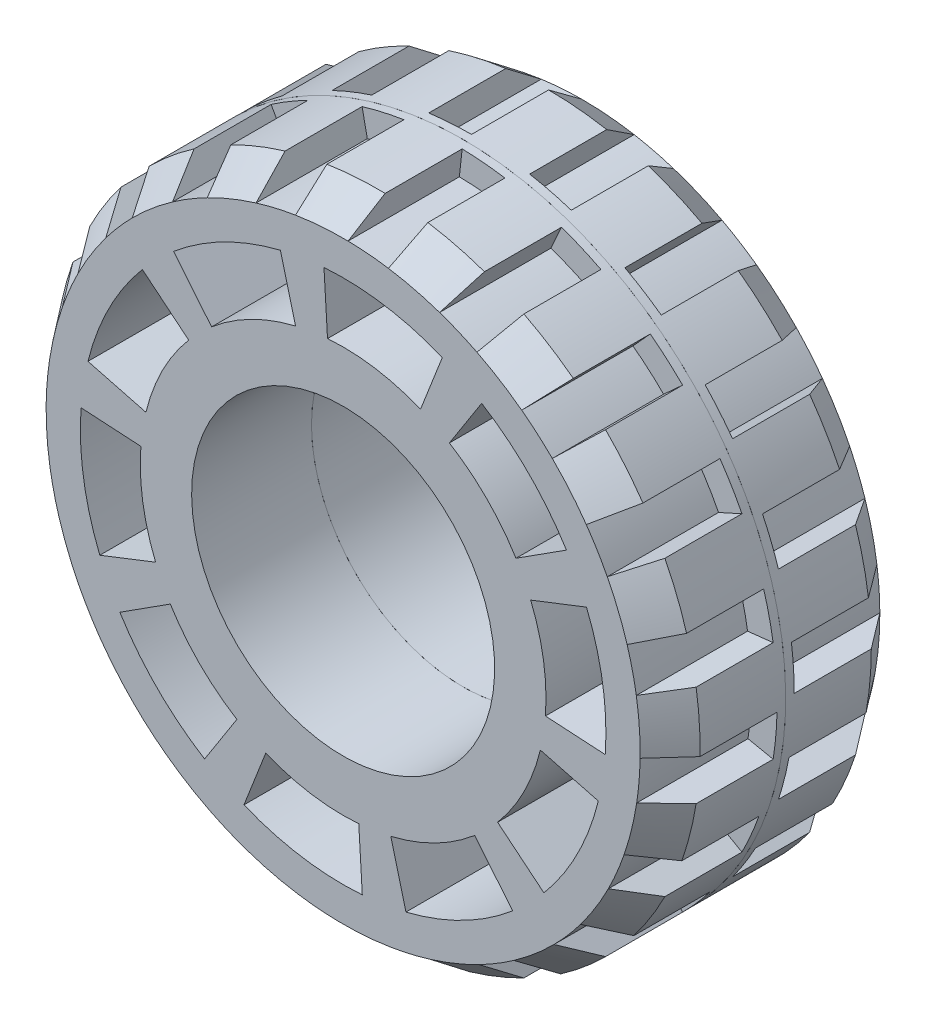
SolidWorks part; units mm, degrees
material "Rubber"
ref_plane "Front Plane" through (0, 0, 0) normal (0, 0, 1) x (1, 0, 0)
ref_plane "Top Plane" through (0, 0, 0) normal (0, 1, 0) x (1, 0, 0)
ref_plane "Right Plane" through (0, 0, 0) normal (1, 0, 0) x (0, 0, -1)
sketch "Sketch2" plane through (0, 0, 0) normal (1, 0, 0) x (0, 0, -1)
  line L0 (0, 8.85) -> (0, 18.85)
  line L1 (0, 18.85) -> (5, 18.85)
  line L2 (5, 18.85) -> (7, 17.35)
  line L3 (0, 8.85) -> (7, 8.85)
  line L4 (7, 17.35) -> (7, 8.85)
  line L5 (-10.899, 0) -> (29.6254, 0) construction
  dimension "D1" = 10
  dimension "D2" = 2.5
  dimension "D3" = 7
  dimension "D4" = 5
  dimension "D5" = 8.85
revolve "Revolve1" add sketch "Sketch2" angle 360 about L5
ref_plane "Plane2" through (0, 0, 0) normal (0, 0, 1) x (1, 0, 0)
sketch "Sketch4" plane through (0, 0, -7) normal (0, 0, -1) x (-1, 0, 0)
  line L0 (14.9457, 3.5) -> (11.5265, 2.75)
  line L1 (14.9457, -3.5) -> (11.5265, -2.75)
  arc A0 (14.9457, 3.5) -> (14.9457, -3.5) centre (0, 0) cw
  arc A1 (11.5265, 2.75) -> (11.5265, -2.75) centre (0, 0) cw
  circle A2 centre (0, 0) radius 18.85 construction
  point P6 (15.35, 0)
  point P7 (11.85, 0)
  dimension "D3" = 3.5
  dimension "D4" = 3.5
  dimension "D1" = 7
  dimension "D2" = 5.5
extrude "Cut-Extrude1" cut sketch "Sketch4" against normal offset from surface (5 mm away) 2 up to face at (8.85, 0, 0)
pattern_circular "CirPattern1" count 10 over 360 about axis through (0, 0, 0) along (0, 0, 1) of "Cut-Extrude1"
sketch "Sketch5" plane through (0, 0, -7) normal (0, 0, -1) x (-1, 0, 0)
  line L0 (0, 18.85) -> (0.0789, 17.1498)
  line L1 (2.5, 18.6835) -> (2.4208, 16.9783)
  circle A0 centre (0, 0) radius 17.35 construction
  circle A1 centre (0, 0) radius 18.85 construction
  circle A2 centre (0, 0) radius 17.35
  circle A3 centre (0, 0) radius 18.85 construction
  arc A4 (0, 18.85) -> (2.5, 18.6835) centre (0, 0) cw
  arc A5 (0.0789, 17.1498) -> (2.4208, 16.9783) centre (0, 0) cw
  point P10 (1.2528, 18.8083)
  point P11 (1.2528, 17.1042)
  circle M43 centre (0, 0) radius 17.35
  dimension "D1" = 2.5
  dimension "D2" = 1.7
  dimension "D3" = 2.3419
extrude "Cut-Extrude2" cut sketch "Sketch5" against normal blind 6.5 contours A4 L0 L1 M43
pattern_circular "CirPattern2" count 20 over 360 about axis through (0, 0, 0) along (0, 0, 1) of "Cut-Extrude2"
mirror "Mirror4" about plane through (0, 0, 0) normal (0, 0, 1) of bodies 107 104
split "Split1" trim tools "Plane2" bodies to split 105 resulting bodies 108 109
move or copy body "Body-Move/Copy1" bodies to move or copy 108 copy no rotation origin (0, 0, 0) rotation axis (0, 0, 1) rotation angle 9
